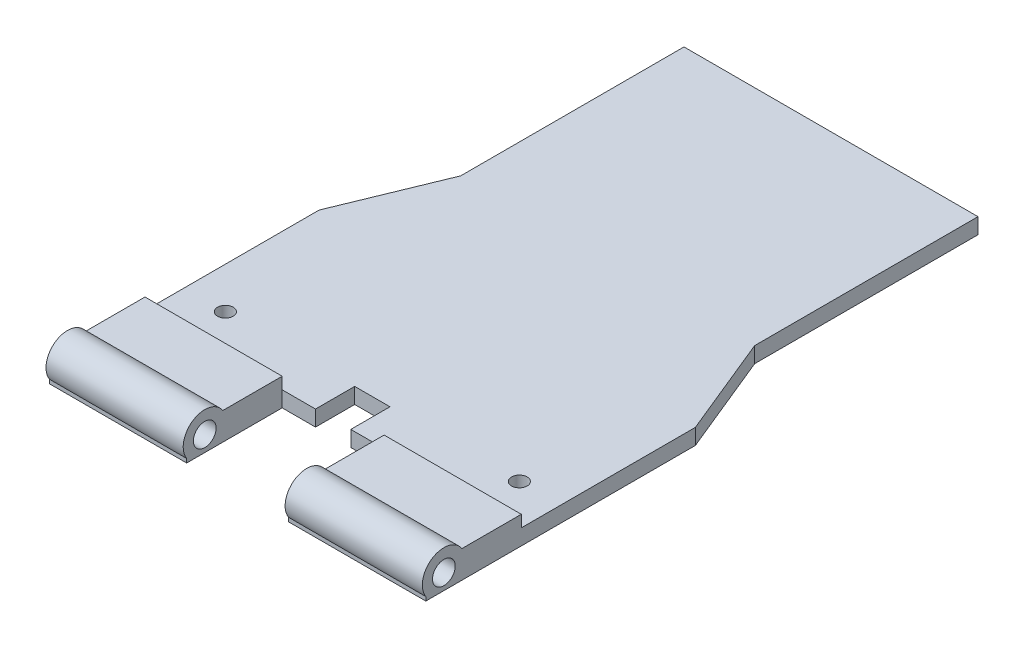
SolidWorks part; units mm, degrees
ref_plane "Front Plane" through (0, 0, 0) normal (0, 0, 1) x (1, 0, 0)
ref_plane "Top Plane" through (0, 0, 0) normal (0, 1, 0) x (1, 0, 0)
ref_plane "Right Plane" through (0, 0, 0) normal (1, 0, 0) x (0, 0, -1)
sketch "Sketch1" plane through (0, 0, 0) normal (0, 1, 0) x (1, 0, 0)
  line L0 (0, 0) -> (0, 23)
  line L1 (0, 23) -> (8.5, 23)
  line L2 (26, 23) -> (26, 0)
  line L3 (26, 0) -> (61, 0)
  line L4 (61, 0) -> (61, 28.8014)
  line L5 (61, 28.8014) -> (50.5, 57.5081) construction
  line L6 (50.5, 93.0296) -> (50.5, 150)
  line L7 (50.5, 150) -> (-24.5, 150)
  line L8 (-24.5, 150) -> (-24.5, 93.0296)
  line L9 (-24.5, 57.5081) -> (-35, 28.8014) construction
  line L10 (-35, 28.8014) -> (-35, 0)
  line L11 (-35, 0) -> (0, 0)
  line L12 (17.5, 23) -> (26, 23)
  line L14 (8.5, 23) -> (8.5, 33)
  line L15 (8.5, 33) -> (17.5, 33)
  line L16 (17.5, 23) -> (17.5, 33)
  line L17 (-35, 28.8014) -> (-35, 67.4062)
  line L18 (-18.8074, 139.3301) -> (15.1926, 139.3301) construction
  line L19 (-18.8074, 139.3301) -> (-18.8074, 64.3301) construction
  line L20 (-18.8074, 64.3301) -> (15.1926, 64.3301) construction
  line L21 (15.1926, 139.3301) -> (15.1926, 64.3301) construction
  line L22 (-18.8074, 139.3301) -> (15.1926, 64.3301) construction
  line L23 (-18.8074, 64.3301) -> (15.1926, 139.3301) construction
  line L24 (-35, 67.4062) -> (-24.5, 93.0296)
  line L25 (13, 185.0477) -> (13, -32.4401) construction
  line L26 (61, 67.4062) -> (50.5, 93.0296)
  line L27 (61, 28.8014) -> (61, 67.4062)
  point P15 (-1.8074, 101.8301)
  point P16 (13, 33)
  point P22 (13, 150)
  point P24 (12, 23)
  dimension "D1" = 26
  dimension "D2" = 23
  dimension "D3" = 75
  dimension "D4" = 96
  dimension "D5" = 38.6048
  dimension "D7" = 9
  dimension "D8" = 10
  dimension "D9" = 75
  dimension "D10" = 34
  dimension "D11" = 150
extrude "Boss-Extrude1" add sketch "Sketch1" along normal blind 3
sketch "Sketch5" plane through (0, 3, 0) normal (0, 1, 0) x (1, 0, 0)
  line L0 (26, 23) -> (26, 0) construction
  line L1 (0, 23) -> (-35, 23)
  line L2 (0, 23) -> (0, 0)
  line L3 (0, 0) -> (-35, 0)
  line L4 (-35, 23) -> (-35, 0)
  line L5 (26, 23) -> (61, 23)
  line L6 (26, 23) -> (26, 0)
  line L7 (26, 0) -> (61, 0)
  line L8 (61, 23) -> (61, 0)
extrude "Boss-Extrude2" add sketch "Sketch5" along normal blind 3
sketch "Sketch6" plane through (-35, 0, 0) normal (-1, 0, 0) x (0, 0, 1)
  line L0 (0, 6) -> (0, 0) construction
  line L1 (0, 6) -> (-3.2478, 6)
  line L2 (-3.2478, 0) -> (0, 0)
  line L3 (0, 6) -> (0, 0)
  arc A0 (-3.2478, 0) -> (-3.2478, 6) centre (-3.2478, 3) ccw
  dimension "D1" = 6
sketch "Sketch11" plane through (-35, 0, 0) normal (-1, 0, 0) x (0, 0, 1)
  line L0 (0, 6) -> (0, 0) construction
  circle A0 centre (-3.2478, 3) radius 2.9
  dimension "D1" = 5.8
  dimension "D2" = 3.2478
sketch "Sketch12" plane through (-35, 0, 0) normal (-1, 0, 0) x (0, 0, 1)
  line L0 (-7.8576, 0) -> (1.3619, 0)
  line L1 (-67.4062, 0) -> (0, 0) construction
  arc A0 (1.3619, 0) -> (-7.8576, 0) centre (-3.2478, 3) ccw
  dimension "D1" = 11
extrude "Boss-Extrude5" add sketch "Sketch12" against normal up to surface (35 mm away) up to face at (0, 3, -13.8)
sketch "Sketch15" plane through (61, 0, 0) normal (1, 0, 0) x (0, 0, -1)
  line L0 (7.8576, 0) -> (-1.3619, 0)
  arc A0 (7.8576, 0) -> (-1.3619, 0) centre (3.2478, 3) ccw
extrude "Boss-Extrude8" add sketch "Sketch15" against normal up to surface (35 mm away) up to face at (26, 3, -13.8)
sketch "Sketch16" plane through (61, 0, 0) normal (1, 0, 0) x (0, 0, -1)
  circle A0 centre (3.2478, 3) radius 2.85
  dimension "D1" = 5.7
extrude "Cut-Extrude1" cut sketch "Sketch11" against normal up to surface (96 mm away)
sketch "Sketch14" plane through (0, 0, 0) normal (0, -1, 0) x (1, 0, 0)
  line L16 (50.5, -93.0296) -> (61, -67.4062)
  line L17 (61, -67.4062) -> (61, 1.3619)
  line L18 (61, 1.3619) -> (26, 1.3619)
  line L19 (26, 1.3619) -> (26, -23)
  line L20 (26, -23) -> (17.5, -23)
  line L21 (17.5, -23) -> (17.5, -33)
  line L22 (17.5, -33) -> (8.5, -33)
  line L23 (8.5, -33) -> (8.5, -23)
  line L24 (8.5, -23) -> (0, -23)
  line L25 (0, -23) -> (0, 1.3619)
  line L26 (0, 1.3619) -> (-35, 1.3619)
  line L27 (-35, 1.3619) -> (-35, -67.4062)
  line L28 (50.5, -93.0296) -> (61, -67.4062)
  line L29 (-24.5, -93.0296) -> (-24.5, -150)
  line L30 (-24.5, -150) -> (50.5, -150)
  line L31 (50.5, -150) -> (50.5, -93.0296)
  line L33 (61, -67.4062) -> (61, 1.3619)
  line L35 (26, 1.3619) -> (26, -23)
  line L36 (26, -23) -> (17.5, -23)
  line L37 (17.5, -23) -> (17.5, -33)
  line L38 (17.5, -33) -> (8.5, -33)
  line L39 (8.5, -33) -> (8.5, -23)
  line L40 (8.5, -23) -> (0, -23)
  line L41 (0, -23) -> (0, 1.3619)
  line L42 (0, 1.3619) -> (-35, 1.3619)
  line L43 (-35, 1.3619) -> (-35, -67.4062)
  line L45 (-24.5, -93.0296) -> (-24.5, -150)
  line L46 (-24.5, -150) -> (50.5, -150)
  line L47 (50.5, -150) -> (50.5, -93.0296)
  line L48 (61, 1.3619) -> (26, 1.3619)
  line L49 (-35, -67.4062) -> (-24.5, -93.0296)
  line L50 (-35, -67.4062) -> (-24.5, -93.0296)
  dimension "D1" = 0
extrude "Boss-Extrude7" add sketch "Sketch14" along normal blind 1
sketch "Sketch17" plane through (0, 3, 0) normal (0, 1, 0) x (1, 0, 0)
  circle A0 centre (-24.5, 33) radius 2
  circle A1 centre (50.5, 33) radius 2
  dimension "D1" = 4
extrude "Cut-Extrude2" cut sketch "Sketch17" against normal blind 10
